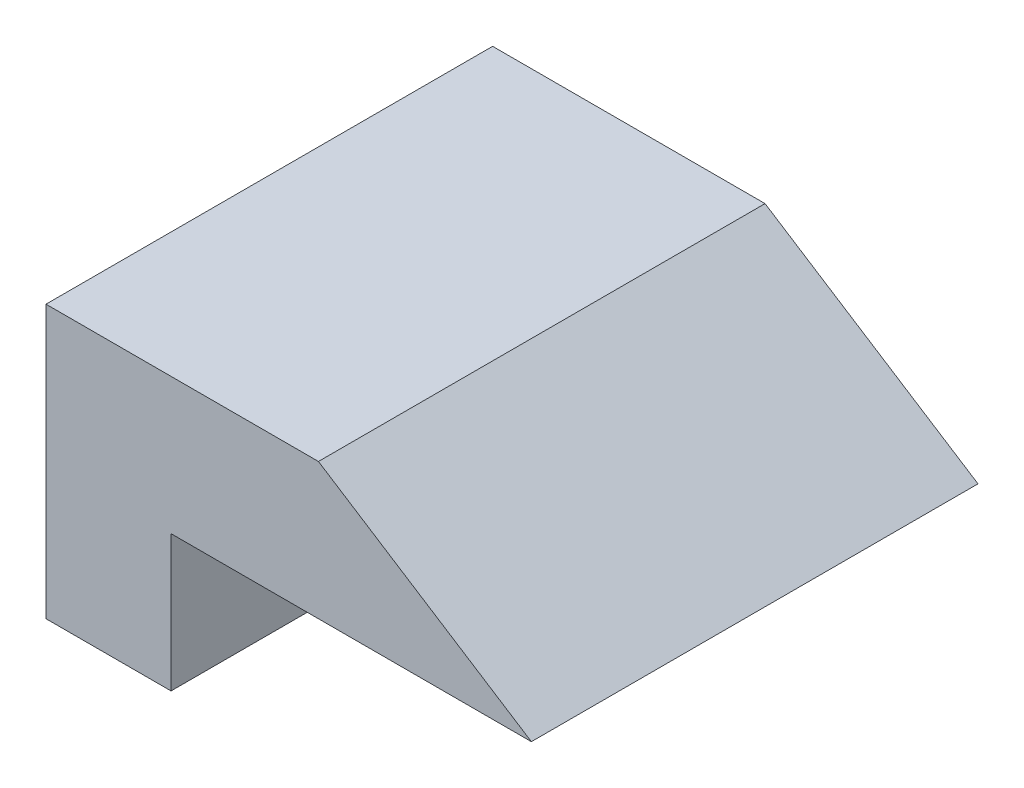
SolidWorks part; units mm, degrees
ref_plane "Alzado" through (0, 0, 0) normal (1, 0, 0) x (0, 1, 0)
ref_plane "Planta" through (0, 0, 0) normal (0, 0, 1) x (0, 1, 0)
ref_plane "Vista lateral" through (0, 0, 0) normal (0, 1, 0) x (-1, 0, 0)
sketch "Croquis1" plane through (0, 0, 0) normal (0, 0, 1) x (0, 1, 0)
  line L0 (-4.9526, 8.0677) -> (3.9188, 8.0677) construction
  line L2 (-3.05, 8.0677) -> (-3.05, 10.8677)
  line L3 (-3.05, 10.8677) -> (3.05, 10.8677)
  line L4 (3.05, 4.7677) -> (3.05, 10.8677)
  line L5 (-3.05, 8.0677) -> (0, 8.0677)
  line L6 (0, 8.0677) -> (0, 0)
  line L7 (0, 0) -> (3.05, 4.7677)
  arc A0 (-3.05, 8.0677) -> (3.05, 8.0677) centre (0, 0) ccw
  point P3 (0, 8.625)
  point P8 (3.05, 8.0677)
  dimension "D1" = 17.25
  dimension "D2" = 3.3
extrude "Saliente-Extruir1" add sketch "Croquis1" along normal blind 10 contours L0 L6 L7 L4 | L5 L0 L4 L3 L2
